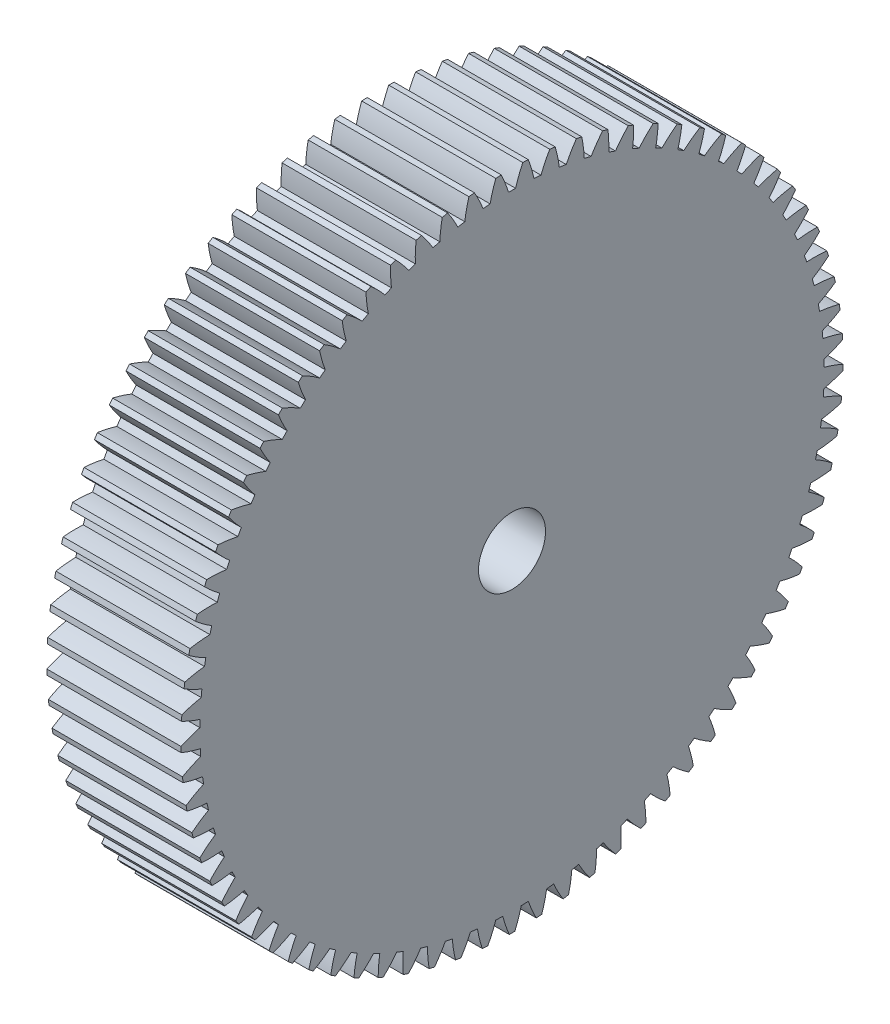
SolidWorks part; units mm, degrees
ref_plane "Plane1" through (0, 0, 0) normal (0, 0, 1) x (1, 0, 0)
ref_plane "Plane2" through (0, 0, 0) normal (0, 1, 0) x (1, 0, 0)
ref_plane "Plane3" through (0, 0, 0) normal (1, 0, 0) x (0, 0, -1)
sketch "HoldingSke" plane through (0, 0, 0) normal (0, 1, 0) x (1, 0, 0)
  line L0 (0, 0) -> (0.4499, -1.9487)
  line L1 (-15, 0) -> (100, 0) construction
  line L2 (0, 0) -> (-2.1039, 2.3779)
  line L3 (0, 0) -> (-11.863, 4.5341)
  line L4 (0, 0) -> (1.9427, 8.4147)
  line L5 (0, 0) -> (-46.8476, -17.4728)
  line L6 (0, 0) -> (-6.6317, -4.4744)
  line L7 (-2.1039, 2.3779) -> (8.6586, 51.2059)
  line L8 (-76.2, 54.61) -> (-75.5, 54.61)
  line L9 (-71.009, 38.7566) -> (-53.1078, 45.2721)
  line L10 (-76.2, 71.12) -> (104.1128, 71.12)
  line L11 (0, 0) -> (-8, 0)
  line L12 (-76.2, 101.6) -> (-76.181, 101.6)
  line L13 (24.9733, 27.94) -> (52.9518, 28.4284)
  line L14 (24.9733, 27.94) -> (24.9743, 27.94)
  line L15 (24.9733, 27.94) -> (100.4006, 29.5858)
  line L16 (-63.627, -0.5) -> (-12.827, -0.5)
  circle A0 centre (0, 0) radius 2
  circle A1 centre (0, 0) radius 18.624
  circle A2 centre (0, 0) radius 37.5
  circle A3 centre (0, 0) radius 2
  dimension "MHD" = 37.248
  dimension "Hub_dia" = 75
  dimension "Bore" = 4
  dimension "MBD" = 4
  dimension "Num_teeth" = 77
  dimension "Pitch" = 2
  dimension "Overall_len" = 50
  dimension "Show_teeth" = 77
  dimension "Thickness" = 8
  dimension "OAL" = 50.0001
  dimension "T_dim" = 0.7
  dimension "Ap" = 20
  dimension "H" = 19.05
  dimension "Pitch_radius" = 180.3128
  dimension "Width" = 8
  dimension "Backlash" = 0.019
  dimension "Addendum_fac" = 1
  dimension "Dedendum_fac" = 1.25
  dimension "Clearance_fac" = 0.25
  dimension "Dedendum_add" = 0.001
  dimension "Module" = 0.5
sketch "BasProSke" plane through (0, 0, 0) normal (0, 1, 0) x (1, 0, 0)
  line L0 (-10, 0) -> (60, 0) construction
  line L1 (0, 0) -> (0, 19.75)
  line L2 (0, 0) -> (8, 0)
  line L3 (8, 0) -> (8, 19.75)
  line L4 (8, 19.75) -> (0, 19.75)
  dimension "Thickness" = 8
  dimension "Diameter" = 39.5
revolve "Base-Revolve" add sketch "BasProSke" angle 360 about L0
sketch "TooCutSke" plane through (0, 0, 0) normal (1, 0, 0) x (0, 0, -1)
  line L1 (0, 0) -> (0, 107) construction
  line L2 (0, 0) -> (-0.4259, 19.2453) construction
  line L3 (0, 0) -> (-1.5701, 38.4613) construction
  line L4 (-0.4259, 19.2453) -> (-0.785, 19.2306) construction
  arc A0 (0.2107, 18.6228) -> (-0.2107, 18.6228) centre (0, 0) ccw
  arc A1 (0.6532, 19.7646) -> (-0.6532, 19.7646) centre (0, 0) ccw
  circle A2 centre (0, 0) radius 19.25 construction
  circle A3 centre (0, 0) radius 18.0891 construction
  arc A4 (-0.2107, 18.6228) -> (-0.6532, 19.7646) centre (-7.5889, 16.4202) ccw
  arc A5 (0.6532, 19.7646) -> (0.2107, 18.6228) centre (7.5889, 16.4202) ccw
  dimension "Root_dia" = 37.248
  dimension "Overcut_dia" = 39.5508
  dimension "Pitch_dia" = 38.5
  dimension "Base_dia" = 36.1782
  dimension "Flank_rad" = 7.7
  dimension "Half_ang" = 2.338
  dimension "Half_CT" = 0.3594
extrude "ToothCut" cut sketch "TooCutSke" along normal through all
fillet "Breaks" [suppressed] radius 0.01
fillet "RootFillets" [suppressed] radius 0.126
pattern_circular "TeethCuts" count 77 every 4.675 about axis through (-10, 0, 0) along (1, 0, 0) of "ToothCut", "RootFillets", "Breaks"
sketch "HubNeaOneSke" plane through (0, 0, 0) normal (-1, 0, 0) x (0, 0, 1)
  circle A0 centre (0, 0) radius 18.624
  dimension "Diameter" = 37.248
extrude "HubNearOne" [suppressed] add sketch "HubNeaOneSke" along normal blind 42.0001
sketch "HubNeaBotSke" plane through (0, 0, 0) normal (-1, 0, 0) x (0, 0, 1)
  circle A0 centre (0, 0) radius 18.624
  dimension "Diameter" = 37.248
extrude "HubNearBoth" [suppressed] add sketch "HubNeaBotSke" along normal blind 21
ref_plane "FarPln" through (8, 0, 0) normal (1, 0, 0) x (0, 0, -1)
sketch "HubFarSke" plane through (8, 0, 0) normal (1, 0, 0) x (0, 0, -1)
  circle A0 centre (0, 0) radius 18.624
  dimension "Diameter" = 37.248
extrude "HubFar" [suppressed] add sketch "HubFarSke" along normal blind 21
sketch "BorSke" plane through (0, 0, 0) normal (1, 0, 0) x (0, 0, -1)
  circle A0 centre (0, 0) radius 2
  dimension "Diameter" = 4
extrude "Bore" cut sketch "BorSke" along normal mid plane 100.0001
sketch "KeySke" plane through (0, 0, 0) normal (1, 0, 0) x (0, 0, -1)
  line L0 (-0.8, 0) -> (-0.8, 2.7)
  line L1 (-0.8, 2.7) -> (0.8, 2.7)
  line L2 (0.8, 2.7) -> (0.8, 0)
  line L3 (0, 0) -> (0, 34) construction
  line L4 (-0.8, 0) -> (0.8, 0)
  dimension "Offset" = 2.7
  dimension "Width" = 1.6
extrude "Keyway" [suppressed] cut sketch "KeySke" along normal mid plane 100.0001
pattern_circular "Keyway2" [suppressed] count 2 every 90 about axis through (-10, 0, 0) along (1, 0, 0)
equation "' \"Module@HoldingSke\" = 6.35"
equation "' \"Num_teeth@HoldingSke\" = 12"
equation "' \"Ap@HoldingSke\" =  20"
equation "' \"Ap@HoldingSke\" = 20"
equation "' \"Width@HoldingSke\" = 0.5 * 25.4"
equation "' \"Hub_dia@HoldingSke\"= 1 * 25.4"
equation "' \"Hub_dia@HoldingSke\" = 1 * 25.4"
equation "' \"Overall_len@HoldingSke\" = 1.0 * 25.4"
equation "' \"Bore@HoldingSke\" = 0.75 * 25.4"
equation "' \"T_dim@HoldingSke\" = 0.1 * 25.4"
equation "' \"Width@KeySke\" = 0.25 * 25.4"
equation "' \"Show_teeth@HoldingSke\" = 13"
equation "' \"Backlash@HoldingSke\" = 0.009 * 25.4"
equation "' \"Addendum_fac@HoldingSke\" = 1.0"
equation "' \"Dedendum_fac@HoldingSke\" = 1.25"
equation "' \"Dedendum_add@HoldingSke\" = 0.00005 * 25.4"
equation "' \"Clearance_fac@HoldingSke\" = 0.25"
equation "\"Pitch@HoldingSke\" = 1 / \"Module@HoldingSke\""
equation "\"Overcut_dia@TooCutSke\" = (\"Num_teeth@HoldingSke\" + 2 * \"Addendum_fac@HoldingSke\") / \"Pitch@HoldingSke\" + 0.002 * 25.4"
equation "\"Pitch_dia@TooCutSke\" = \"Num_teeth@HoldingSke\" / \"Pitch@HoldingSke\""
equation "\"Base_dia@TooCutSke\" = \"Num_teeth@HoldingSke\" / \"Pitch@HoldingSke\" * cos((\"Ap@HoldingSke\"  * 3.14159265 / 180))"
equation "\"Root_dia@TooCutSke\" = (\"Num_teeth@HoldingSke\" + 2) / \"Pitch@HoldingSke\" - 2 * (\"Addendum_fac@HoldingSke\" + \"Dedendum_fac@HoldingSke\") / \"Pitch@HoldingSke\" - \"Dedendum_add@HoldingSke\" * 2"
equation "\"Half_ang@TooCutSke\" = 180 / \"Num_teeth@HoldingSke\""
equation "\"Half_CT@TooCutSke\" = \"Num_teeth@HoldingSke\" / \"Pitch@HoldingSke\" * sin((3.14159265 / 2 / \"Num_teeth@HoldingSke\")) / 2 - 7 * \"Backlash@HoldingSke\" / 4"
equation "\"Flank_rad@TooCutSke\" = \"Num_teeth@HoldingSke\" / \"Pitch@HoldingSke\" / 5"
equation "\"Radius@RootFillets\" = \"Clearance_fac@HoldingSke\" / \"Pitch@HoldingSke\" + \"Dedendum_add@HoldingSke\""
equation "\"Break_rad@Breaks\" = 0.02 / \"Pitch@HoldingSke\""
equation "\"Thickness@HoldingSke\" = \"Width@HoldingSke\""
equation "\"OAL@HoldingSke\" = \"Thickness@HoldingSke\""
equation "\"MHD@HoldingSke\" = (\"Num_teeth@HoldingSke\" + 2) / \"Pitch@HoldingSke\" - 2 * (\"Addendum_fac@HoldingSke\" + \"Dedendum_fac@HoldingSke\")  / \"Pitch@HoldingSke\" - \"Dedendum_add@HoldingSke\" * 2"
equation "\"MBD@HoldingSke\" = (\"Num_teeth@HoldingSke\" + 2) / \"Pitch@HoldingSke\" - 2 * (\"Addendum_fac@HoldingSke\" + \"Dedendum_fac@HoldingSke\")  / \"Pitch@HoldingSke\" - \"Dedendum_add@HoldingSke\" * 2 - 0.002 * 25.4"
equation "\"MHD@HoldingSke\" = ((sgn( \"MHD@HoldingSke\" - \"Hub_dia@HoldingSke\" )-1)*( \"MHD@HoldingSke\" - \"Hub_dia@HoldingSke\" ))/-2+ \"Hub_dia@HoldingSke\""
equation "\"MBD@HoldingSke\" = ((sgn( \"MBD@HoldingSke\" - \"Bore@HoldingSke\" )-1)*( \"MBD@HoldingSke\" - \"Bore@HoldingSke\" ))/-2+ \"Bore@HoldingSke\""
equation "\"OAL@HoldingSke\" = ((sgn( \"OAL@HoldingSke\" - \"Overall_len@HoldingSke\" )+1)*( \"OAL@HoldingSke\" - \"Overall_len@HoldingSke\" ))/2 + \"Overall_len@HoldingSke\" + 0.000002 * 25.4"
equation "\"Num_teeth@TeethCuts\" = int( \"Show_teeth@HoldingSke\" ) + 1"
equation "\"Num_teeth@TeethCuts\" = ((sgn( \"Num_teeth@TeethCuts\" - \"Num_teeth@HoldingSke\" )-1)*( \"Num_teeth@TeethCuts\" - \"Num_teeth@HoldingSke\" ))/-2+ \"Num_teeth@HoldingSke\""
equation "\"Num_teeth@TeethCuts\" = ((sgn( \"Num_teeth@TeethCuts\" - 2.0)+1)*( \"Num_teeth@TeethCuts\" - 2.0))/2 +2.0"
equation "\"Angle@TeethCuts\" = 360.0 / \"Num_teeth@HoldingSke\""
equation "\"Diameter@BasProSke\" = (\"Num_teeth@HoldingSke\" + 2 * \"Addendum_fac@HoldingSke\") / \"Pitch@HoldingSke\""
equation "\"Thickness@BasProSke\"  = \"Thickness@HoldingSke\""
equation "' \"Fillet_rad@BasProSke\" =  \"Thickness@HoldingSke\" * 0.05"
equation "' \"Fillet_rad@BasProSke\" = \"Thickness@HoldingSke\" * 0.05"
equation "\"MHD@HoldingSke\" = ((sgn( \"MHD@HoldingSke\" - \"Root_dia@TooCutSke\" )-1)*( \"MHD@HoldingSke\" - \"Root_dia@TooCutSke\" ))/-2+ \"Root_dia@TooCutSke\""
equation "\"Diameter@HubNeaOneSke\" = \"MHD@HoldingSke\""
equation "\"Length@HubNearOne\" = \"OAL@HoldingSke\" - \"Thickness@BasProSke\""
equation "\"Diameter@HubNeaBotSke\" = \"MHD@HoldingSke\""
equation "\"Length@HubNearBoth\" = ( \"OAL@HoldingSke\" - \"Thickness@BasProSke\" ) / 2.0"
equation "\"Thickness@FarPln\" = \"Thickness@BasProSke\""
equation "\"Diameter@HubFarSke\" = \"MHD@HoldingSke\""
equation "\"Length@HubFar\" = ( \"OAL@HoldingSke\" - \"Thickness@BasProSke\" ) / 2.0"
equation "\"Diameter@BorSke\" = \"MBD@HoldingSke\""
equation "\"D1@Bore\" = \"OAL@HoldingSke\" * 2.0"
equation "\"D1@Keyway\" = \"OAL@HoldingSke\" * 2.0"
equation "\"Offset@KeySke\" = \"T_dim@HoldingSke\" + \"MBD@HoldingSke\" / 2.0"
